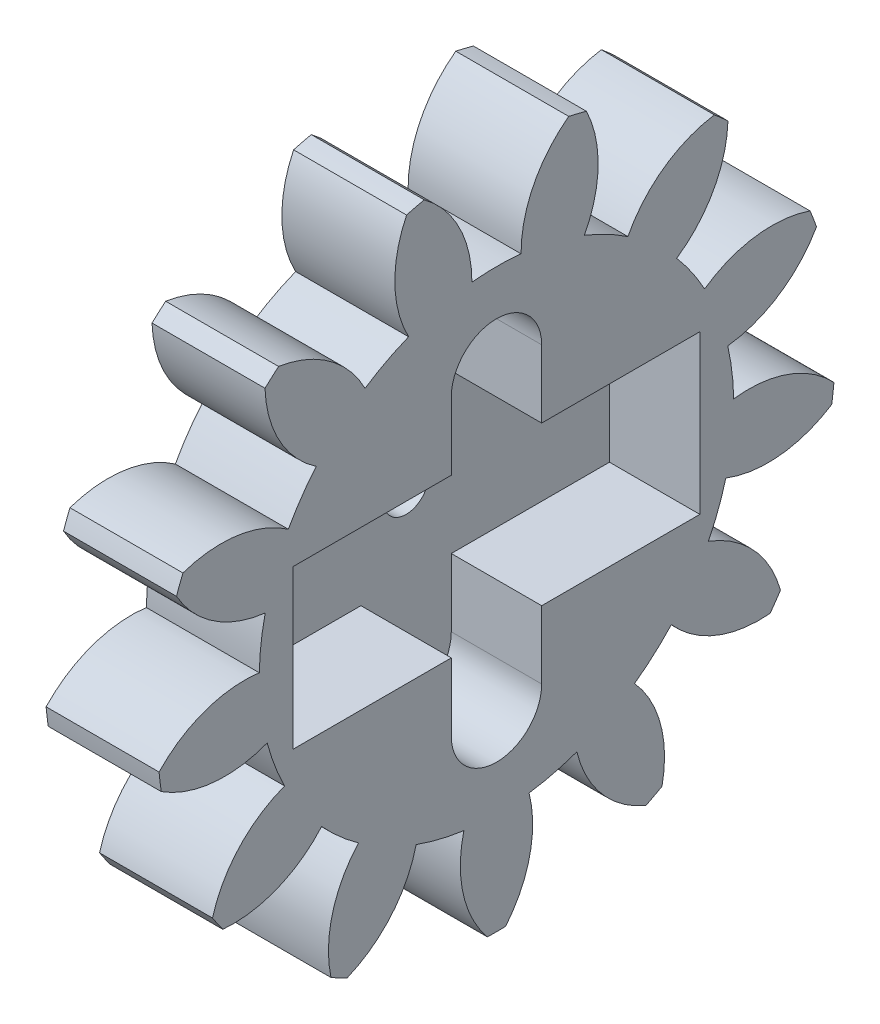
SolidWorks part; units mm, degrees
ref_plane "Plane1" through (0, 0, 0) normal (0, 0, 1) x (1, 0, 0)
ref_plane "Plane2" through (0, 0, 0) normal (0, 1, 0) x (1, 0, 0)
ref_plane "Plane3" through (0, 0, 0) normal (1, 0, 0) x (0, 0, -1)
sketch "HoldingSke" plane through (0, 0, 0) normal (0, 1, 0) x (1, 0, 0)
  line L0 (0, 0) -> (0.4872, -0.1125)
  line L1 (-15, 0) -> (100, 0) construction
  line L2 (0, 0) -> (-2.1039, 2.3779)
  line L3 (0, 0) -> (-11.863, 4.5341)
  line L4 (0, 0) -> (8.4147, 1.9427)
  line L5 (0, 0) -> (-46.8476, -17.4728)
  line L6 (0, 0) -> (-4.1448, -2.7965)
  line L7 (-2.1039, 2.3779) -> (8.6586, 51.2059)
  line L8 (-76.2, 54.61) -> (-75.9, 54.61)
  line L9 (-71.009, 38.7566) -> (-53.1078, 45.2721)
  line L10 (-76.2, 71.12) -> (104.1128, 71.12)
  line L11 (0, 0) -> (-5, 0)
  line L12 (-76.2, 101.6) -> (-76.133, 101.6)
  line L13 (24.9733, 27.94) -> (52.9518, 28.4284)
  line L14 (24.9733, 27.94) -> (24.9743, 27.94)
  line L15 (24.9733, 27.94) -> (100.4006, 29.5858)
  line L16 (-63.627, -2) -> (-12.827, -2)
  circle A0 centre (0, 0) radius 1
  circle A1 centre (0, 0) radius 10.499
  circle A2 centre (0, 0) radius 37.5
  circle A3 centre (0, 0) radius 1
  dimension "MHD" = 20.998
  dimension "Hub_dia" = 75
  dimension "Bore" = 2
  dimension "MBD" = 2
  dimension "Num_teeth" = 13
  dimension "Pitch_radius" = 180.3128
  dimension "Pitch" = 0.5
  dimension "Width" = 5
  dimension "Overall_len" = 50
  dimension "Show_teeth" = 13
  dimension "Thickness" = 5
  dimension "OAL" = 50.0001
  dimension "T_dim" = 0.3
  dimension "Ap" = 20
  dimension "H" = 19.05
  dimension "Backlash" = 0.067
  dimension "Addendum_fac" = 1
  dimension "Dedendum_fac" = 1.25
  dimension "Clearance_fac" = 0.25
  dimension "Dedendum_add" = 0.001
  dimension "Module" = 2
sketch "BasProSke" plane through (0, 0, 0) normal (0, 1, 0) x (1, 0, 0)
  line L0 (-10, 0) -> (60, 0) construction
  line L1 (0, 0) -> (0, 15)
  line L2 (0, 0) -> (5, 0)
  line L3 (5, 0) -> (5, 15)
  line L4 (5, 15) -> (0, 15)
  dimension "Diameter" = 30
  dimension "Thickness" = 5
revolve "Base-Revolve" add sketch "BasProSke" angle 360 about L0
sketch "TooCutSke" plane through (0, 0, 0) normal (1, 0, 0) x (0, 0, -1)
  line L1 (0, 0) -> (0, 107) construction
  line L2 (0, 0) -> (-1.6841, 12.8905) construction
  line L3 (0, 0) -> (-6.1834, 25.087) construction
  line L4 (-1.6841, 12.8905) -> (-3.0917, 12.5435) construction
  arc A0 (1.0882, 10.4424) -> (-1.0882, 10.4424) centre (0, 0) ccw
  arc A1 (3.2249, 14.6752) -> (-3.2249, 14.6752) centre (0, 0) ccw
  circle A2 centre (0, 0) radius 13 construction
  circle A3 centre (0, 0) radius 12.216 construction
  arc A4 (-1.0882, 10.4424) -> (-3.2249, 14.6752) centre (-6.2882, 10.4733) ccw
  arc A5 (3.2249, 14.6752) -> (1.0882, 10.4424) centre (6.2882, 10.4733) ccw
  dimension "Root_dia" = 20.998
  dimension "Overcut_dia" = 30.0508
  dimension "Pitch_dia" = 26
  dimension "Base_dia" = 24.432
  dimension "Flank_rad" = 5.2
  dimension "Half_ang" = 13.846
  dimension "Half_CT" = 1.4497
extrude "ToothCut" cut sketch "TooCutSke" along normal through all
fillet "Breaks" [suppressed] radius 0.04
fillet "RootFillets" [suppressed] radius 0.501
pattern_circular "TeethCuts" count 13 every 27.692 about axis through (-10, 0, 0) along (1, 0, 0) of "ToothCut", "RootFillets", "Breaks"
sketch "HubNeaOneSke" plane through (0, 0, 0) normal (-1, 0, 0) x (0, 0, 1)
  circle A0 centre (0, 0) radius 10.499
  dimension "Diameter" = 20.998
extrude "HubNearOne" [suppressed] add sketch "HubNeaOneSke" along normal blind 45.0001
sketch "HubNeaBotSke" plane through (0, 0, 0) normal (-1, 0, 0) x (0, 0, 1)
  circle A0 centre (0, 0) radius 10.499
  dimension "Diameter" = 20.998
extrude "HubNearBoth" [suppressed] add sketch "HubNeaBotSke" along normal blind 22.5
ref_plane "FarPln" through (5, 0, 0) normal (1, 0, 0) x (0, 0, -1)
sketch "HubFarSke" plane through (5, 0, 0) normal (1, 0, 0) x (0, 0, -1)
  circle A0 centre (0, 0) radius 10.499
  dimension "Diameter" = 20.998
extrude "HubFar" [suppressed] add sketch "HubFarSke" along normal blind 22.5
sketch "BorSke" plane through (0, 0, 0) normal (1, 0, 0) x (0, 0, -1)
  circle A0 centre (0, 0) radius 1
  dimension "Diameter" = 2
extrude "Bore" cut sketch "BorSke" along normal mid plane 100.0001
sketch "KeySke" plane through (0, 0, 0) normal (1, 0, 0) x (0, 0, -1)
  line L0 (-0.4, 0) -> (-0.4, 1.3)
  line L1 (-0.4, 1.3) -> (0.4, 1.3)
  line L2 (0.4, 1.3) -> (0.4, 0)
  line L3 (0, 0) -> (0, 34) construction
  line L4 (-0.4, 0) -> (0.4, 0)
  dimension "Offset" = 1.3
  dimension "Width" = 0.8
extrude "Keyway" [suppressed] cut sketch "KeySke" along normal mid plane 100.0001
pattern_circular "Keyway2" [suppressed] count 2 every 90 about axis through (-10, 0, 0) along (1, 0, 0)
sketch "Sketch1" plane through (5, 0, 0) normal (1, 0, 0) x (0, 0, -1)
  line L0 (0, 8.5) -> (0, -4.9314) construction
  line L1 (2, 6.5) -> (2, 3.5)
  line L2 (2, 3.5) -> (9, 3.5)
  line L3 (9, 3.5) -> (9, -3.5)
  line L4 (-0.2156, 0) -> (0.2156, 0) construction
  line L5 (9, 0) -> (-9, 0) construction
  line L6 (2, -3.5) -> (9, -3.5)
  line L7 (2, -6.5) -> (2, -3.5)
  line L8 (-2, -6.5) -> (-2, -3.5)
  line L9 (-2, -3.5) -> (-9, -3.5)
  line L10 (-9, 3.5) -> (-9, -3.5)
  line L11 (-2, 3.5) -> (-9, 3.5)
  line L12 (-2, 6.5) -> (-2, 3.5)
  arc A0 (-2, 6.5) -> (2, 6.5) centre (0, 6.5) cw
  arc A1 (-2, -6.5) -> (2, -6.5) centre (0, -6.5) ccw
  point P17 (0, 0)
  dimension "D1" = 18
  dimension "D2" = 7
  dimension "D3" = 4
extrude "Cut-Extrude1" cut sketch "Sketch1" against normal blind 4
equation "' \"Module@HoldingSke\" = 6.35"
equation "' \"Num_teeth@HoldingSke\" = 12"
equation "' \"Ap@HoldingSke\" =  20"
equation "' \"Width@HoldingSke\" = 0.5 * 25.4"
equation "' \"Hub_dia@HoldingSke\"= 1 * 25.4"
equation "' \"Overall_len@HoldingSke\" = 1.0 * 25.4"
equation "' \"Bore@HoldingSke\" = 0.75 * 25.4"
equation "' \"T_dim@HoldingSke\" = 0.1 * 25.4"
equation "' \"Width@KeySke\" = 0.25 * 25.4"
equation "' \"Show_teeth@HoldingSke\" = 13"
equation "' \"Backlash@HoldingSke\" = 0.009 * 25.4"
equation "' \"Addendum_fac@HoldingSke\" = 1.0"
equation "' \"Dedendum_fac@HoldingSke\" = 1.25"
equation "' \"Dedendum_add@HoldingSke\" = 0.00005 * 25.4"
equation "' \"Clearance_fac@HoldingSke\" = 0.25"
equation "\"Pitch@HoldingSke\" = 1 / \"Module@HoldingSke\""
equation "\"Overcut_dia@TooCutSke\" = (\"Num_teeth@HoldingSke\" + 2 * \"Addendum_fac@HoldingSke\") / \"Pitch@HoldingSke\" + 0.002 * 25.4"
equation "\"Pitch_dia@TooCutSke\" = \"Num_teeth@HoldingSke\" / \"Pitch@HoldingSke\""
equation "\"Base_dia@TooCutSke\" = \"Num_teeth@HoldingSke\" / \"Pitch@HoldingSke\" * cos((\"Ap@HoldingSke\"  * 3.14159265 / 180))"
equation "\"Root_dia@TooCutSke\" = (\"Num_teeth@HoldingSke\" + 2) / \"Pitch@HoldingSke\" - 2 * (\"Addendum_fac@HoldingSke\" + \"Dedendum_fac@HoldingSke\") / \"Pitch@HoldingSke\" - \"Dedendum_add@HoldingSke\" * 2"
equation "\"Half_ang@TooCutSke\" = 180 / \"Num_teeth@HoldingSke\""
equation "\"Half_CT@TooCutSke\" = \"Num_teeth@HoldingSke\" / \"Pitch@HoldingSke\" * sin((3.14159265 / 2 / \"Num_teeth@HoldingSke\")) / 2 - 7 * \"Backlash@HoldingSke\" / 4"
equation "\"Flank_rad@TooCutSke\" = \"Num_teeth@HoldingSke\" / \"Pitch@HoldingSke\" / 5"
equation "\"Radius@RootFillets\" = \"Clearance_fac@HoldingSke\" / \"Pitch@HoldingSke\" + \"Dedendum_add@HoldingSke\""
equation "\"Break_rad@Breaks\" = 0.02 / \"Pitch@HoldingSke\""
equation "\"Thickness@HoldingSke\" = \"Width@HoldingSke\""
equation "\"OAL@HoldingSke\" = \"Thickness@HoldingSke\""
equation "\"MHD@HoldingSke\" = (\"Num_teeth@HoldingSke\" + 2) / \"Pitch@HoldingSke\" - 2 * (\"Addendum_fac@HoldingSke\" + \"Dedendum_fac@HoldingSke\")  / \"Pitch@HoldingSke\" - \"Dedendum_add@HoldingSke\" * 2"
equation "\"MBD@HoldingSke\" = (\"Num_teeth@HoldingSke\" + 2) / \"Pitch@HoldingSke\" - 2 * (\"Addendum_fac@HoldingSke\" + \"Dedendum_fac@HoldingSke\")  / \"Pitch@HoldingSke\" - \"Dedendum_add@HoldingSke\" * 2 - 0.002 * 25.4"
equation "\"MHD@HoldingSke\" = ((sgn( \"MHD@HoldingSke\" - \"Hub_dia@HoldingSke\" )-1)*( \"MHD@HoldingSke\" - \"Hub_dia@HoldingSke\" ))/-2+ \"Hub_dia@HoldingSke\""
equation "\"MBD@HoldingSke\" = ((sgn( \"MBD@HoldingSke\" - \"Bore@HoldingSke\" )-1)*( \"MBD@HoldingSke\" - \"Bore@HoldingSke\" ))/-2+ \"Bore@HoldingSke\""
equation "\"OAL@HoldingSke\" = ((sgn( \"OAL@HoldingSke\" - \"Overall_len@HoldingSke\" )+1)*( \"OAL@HoldingSke\" - \"Overall_len@HoldingSke\" ))/2 + \"Overall_len@HoldingSke\" + 0.000002 * 25.4"
equation "\"Num_teeth@TeethCuts\" = int( \"Show_teeth@HoldingSke\" ) + 1"
equation "\"Num_teeth@TeethCuts\" = ((sgn( \"Num_teeth@TeethCuts\" - \"Num_teeth@HoldingSke\" )-1)*( \"Num_teeth@TeethCuts\" - \"Num_teeth@HoldingSke\" ))/-2+ \"Num_teeth@HoldingSke\""
equation "\"Num_teeth@TeethCuts\" = ((sgn( \"Num_teeth@TeethCuts\" - 2.0)+1)*( \"Num_teeth@TeethCuts\" - 2.0))/2 +2.0"
equation "\"Angle@TeethCuts\" = 360.0 / \"Num_teeth@HoldingSke\""
equation "\"Diameter@BasProSke\" = (\"Num_teeth@HoldingSke\" + 2 * \"Addendum_fac@HoldingSke\") / \"Pitch@HoldingSke\""
equation "\"Thickness@BasProSke\"  = \"Thickness@HoldingSke\""
equation "' \"Fillet_rad@BasProSke\" =  \"Thickness@HoldingSke\" * 0.05"
equation "\"MHD@HoldingSke\" = ((sgn( \"MHD@HoldingSke\" - \"Root_dia@TooCutSke\" )-1)*( \"MHD@HoldingSke\" - \"Root_dia@TooCutSke\" ))/-2+ \"Root_dia@TooCutSke\""
equation "\"Diameter@HubNeaOneSke\" = \"MHD@HoldingSke\""
equation "\"Length@HubNearOne\" = \"OAL@HoldingSke\" - \"Thickness@BasProSke\""
equation "\"Diameter@HubNeaBotSke\" = \"MHD@HoldingSke\""
equation "\"Length@HubNearBoth\" = ( \"OAL@HoldingSke\" - \"Thickness@BasProSke\" ) / 2.0"
equation "\"Thickness@FarPln\" = \"Thickness@BasProSke\""
equation "\"Diameter@HubFarSke\" = \"MHD@HoldingSke\""
equation "\"Length@HubFar\" = ( \"OAL@HoldingSke\" - \"Thickness@BasProSke\" ) / 2.0"
equation "\"Diameter@BorSke\" = \"MBD@HoldingSke\""
equation "\"D1@Bore\" = \"OAL@HoldingSke\" * 2.0"
equation "\"D1@Keyway\" = \"OAL@HoldingSke\" * 2.0"
equation "\"Offset@KeySke\" = \"T_dim@HoldingSke\" + \"MBD@HoldingSke\" / 2.0"
